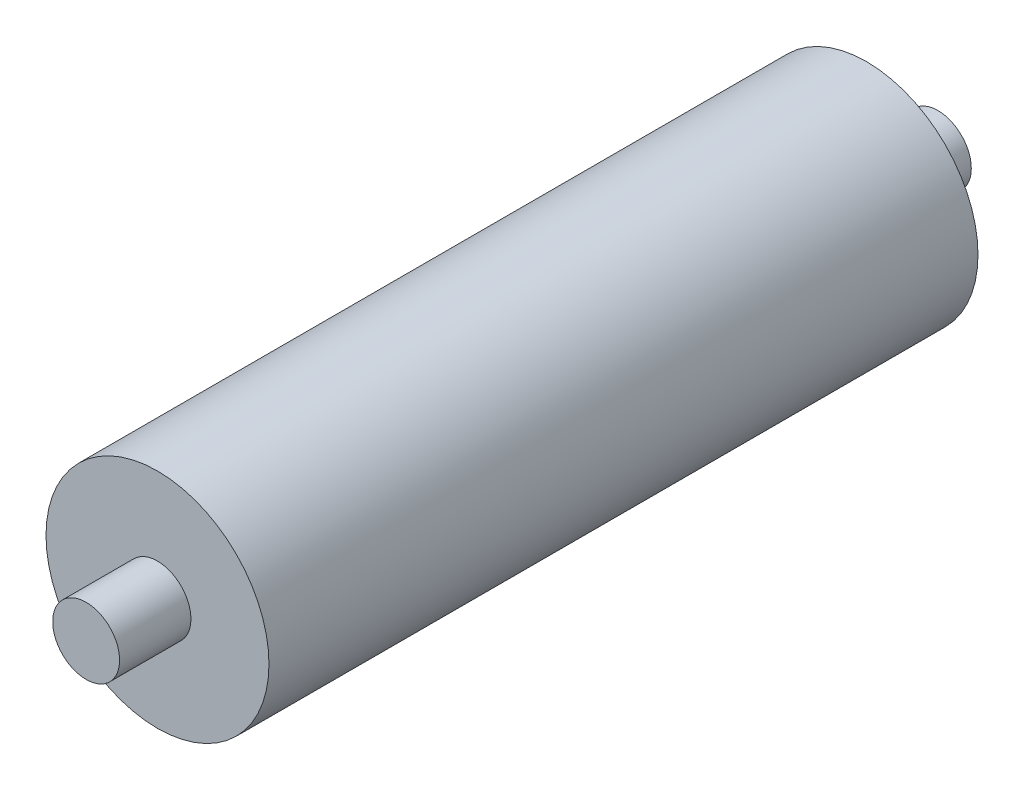
SolidWorks part; units mm, degrees
material "1060 Alloy"
ref_plane "Front Plane" through (0, 0, 0) normal (0, 0, 1) x (1, 0, 0)
ref_plane "Top Plane" through (0, 0, 0) normal (0, 1, 0) x (1, 0, 0)
ref_plane "Right Plane" through (0, 0, 0) normal (1, 0, 0) x (0, 0, -1)
sketch "Sketch1" plane through (0, 0, 0) normal (0, 0, 1) x (1, 0, 0)
  circle A0 centre (-8.994, 14.4897) radius 50
  dimension "D1" = 100
extrude "Boss-Extrude1" add sketch "Sketch1" against normal blind 318
sketch "Sketch2" plane through (0, 0, 0) normal (0, 0, 1) x (1, 0, 0)
  circle A0 centre (-8.994, 14.4897) radius 15
  dimension "D1" = 30
extrude "Boss-Extrude2" add sketch "Sketch2" along normal blind 32
ref_plane "Plane1" through (0, 0, -159) normal (0, 0, 1) x (1, 0, 0)
mirror "Mirror1" about plane through (0, 0, -159) normal (0, 0, 1) of "Boss-Extrude2"
